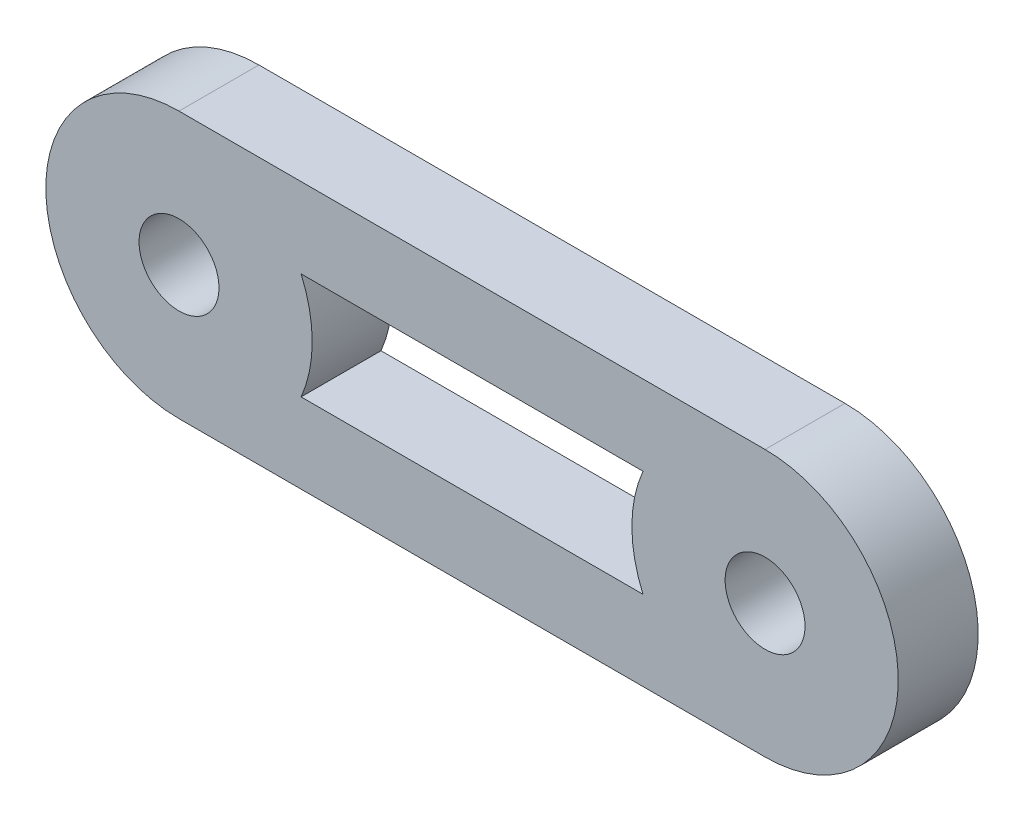
SolidWorks part; units mm, degrees
material "1060 Alloy"
ref_plane "Front Plane" through (0, 0, 0) normal (0, 0, 1) x (1, 0, 0)
ref_plane "Top Plane" through (0, 0, 0) normal (0, 1, 0) x (1, 0, 0)
ref_plane "Right Plane" through (0, 0, 0) normal (1, 0, 0) x (0, 0, -1)
sketch "Sketch1" plane through (0, 0, 0) normal (0, 0, 1) x (1, 0, 0)
  line L0 (0, 0) -> (22, 0)
  line L1 (0, -5) -> (22, -5)
  line L2 (0, 5) -> (22, 5)
  circle A0 centre (22, 0) radius 1.5
  circle A1 centre (0, 0) radius 1.5
  arc A2 (0, -5) -> (0, 5) centre (0, 0) cw
  arc A3 (22, -5) -> (22, 5) centre (22, 0) ccw
  dimension "D1" = 3
extrude "Extrude1" add sketch "Sketch1" along normal blind 3
sketch "Sketch2" plane through (0, 0, 3) normal (0, 0, 1) x (1, 0, 0)
  line L4 (0, -2) -> (22, -2)
  line L5 (22, 2) -> (0, 2)
  line L6 (4.5826, -2) -> (17.4174, -2)
  line L7 (17.4174, 2) -> (4.5826, 2)
  arc A2 (4.5826, -2) -> (4.5826, 2) centre (0, 0) ccw
  arc A3 (17.4174, 2) -> (17.4174, -2) centre (22, 0) ccw
  arc A4 (22, -2) -> (22, 2) centre (22, 0) ccw
  arc A5 (0, 2) -> (0, -2) centre (0, 0) ccw
  dimension "D1" = 3
extrude "Cut-Extrude1" cut sketch "Sketch2" against normal blind 10
move or copy body "Body-Move/Copy1" [suppressed] bodies to move or copy 103
move or copy body "Body-Move/Copy2" [suppressed] bodies to move or copy 103
